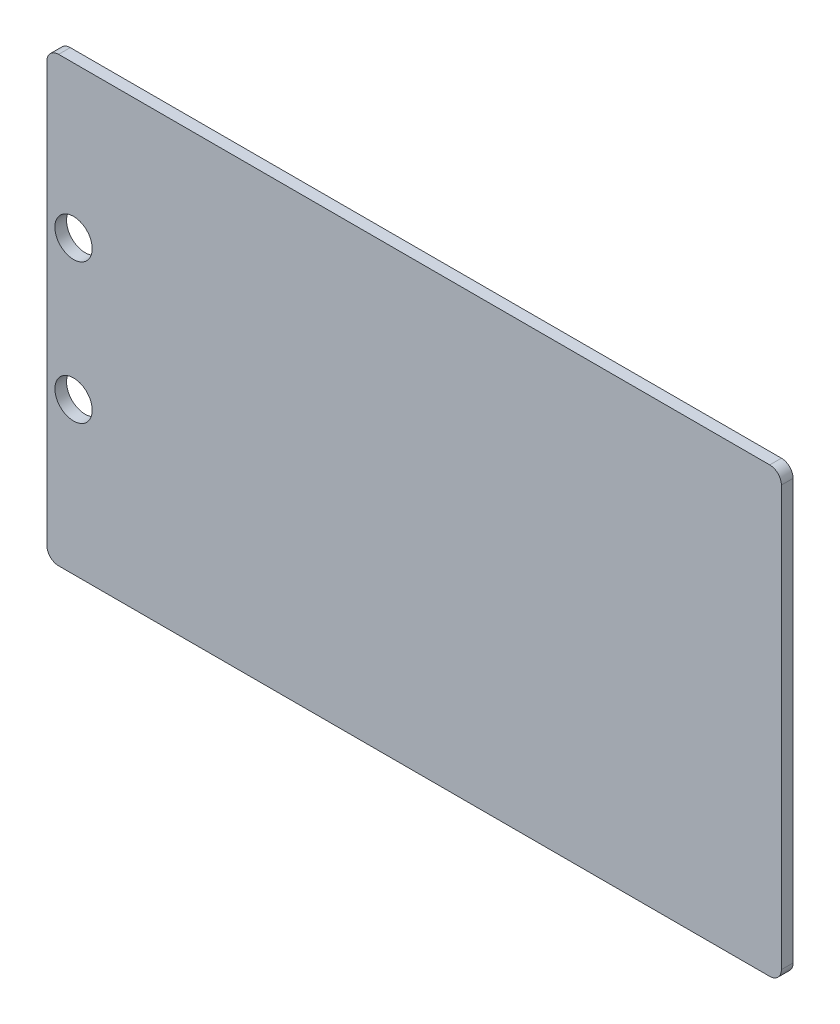
SolidWorks part; units mm, degrees
material "Thornel Mat VMA"
ref_plane "前视基准面" through (0, 0, 0) normal (0, 0, 1) x (1, 0, 0)
ref_plane "上视基准面" through (0, 0, 0) normal (0, 1, 0) x (1, 0, 0)
ref_plane "右视基准面" through (0, 0, 0) normal (1, 0, 0) x (0, 0, -1)
sketch "草图1" plane through (0, 0, 0) normal (0, 0, 1) x (1, 0, 0)
  line L1 (-31.5, 19) -> (31.5, 19)
  line L2 (-31.5, 19) -> (-31.5, -19)
  line L3 (-31.5, -19) -> (31.5, -19)
  line L4 (31.5, 19) -> (31.5, -19)
  line L5 (-31.5, 19) -> (31.5, -19) construction
  line L6 (-31.5, -19) -> (31.5, 19) construction
  point P0 (0, 0)
  dimension "D1" = 38
  dimension "D2" = 63
extrude "凸台-拉伸1" add sketch "草图1" along normal blind 1
fillet "圆角1" radius 1 4 edges at (31.5, 19, 0.5) (31.5, -19, 0.5) (-31.5, -19, 0.5) (-31.5, 19, 0.5)
sketch "草图2" plane through (0, 0, 1) normal (0, 0, 1) x (1, 0, 0)
  circle A0 centre (-29.2189, -6) radius 1.6 construction
  circle A1 centre (-29.2189, 6) radius 1.6 construction
  circle A2 centre (-29.2189, -6) radius 1.6
  circle A3 centre (-29.2189, 6) radius 1.6
extrude "切除-拉伸1" cut sketch "草图2" against normal blind 2
